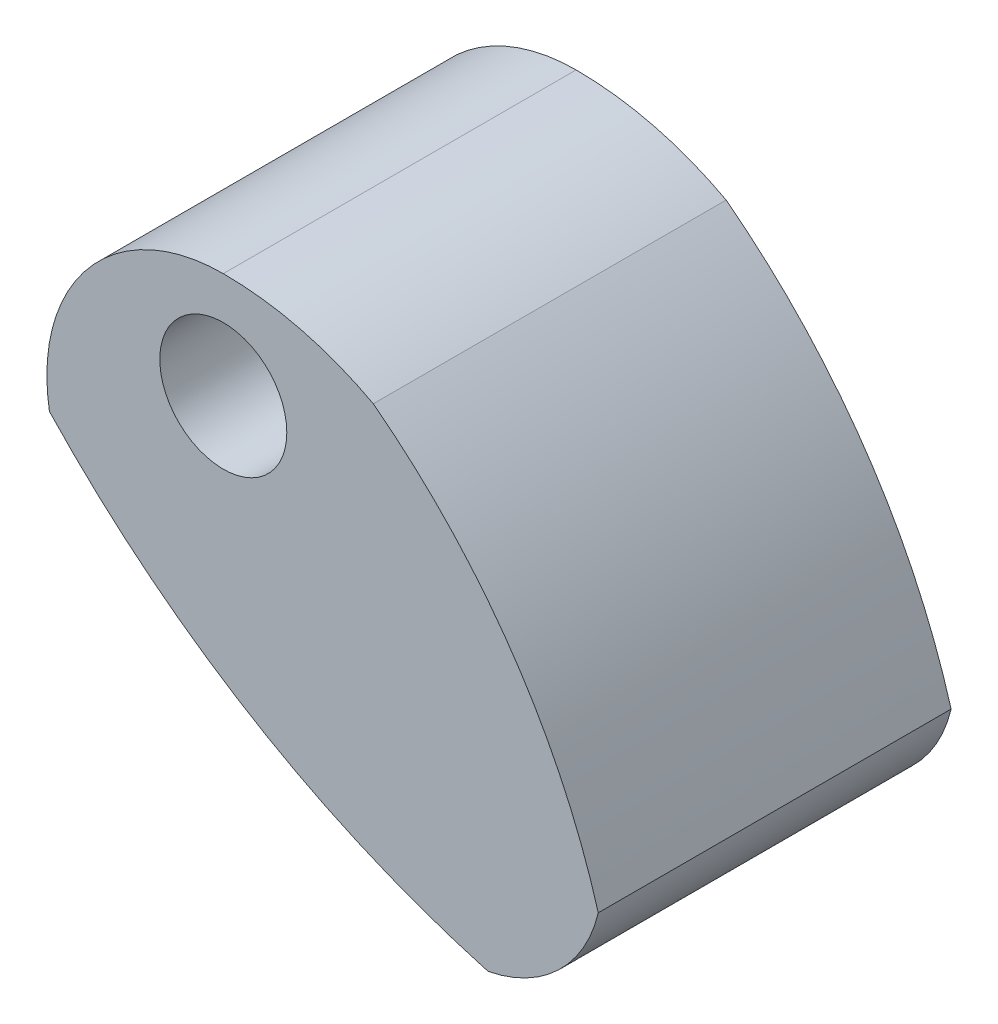
SolidWorks part; units mm, degrees
ref_plane "Front Plane" through (0, 0, 0) normal (0, 0, 1) x (1, 0, 0)
ref_plane "Top Plane" through (0, 0, 0) normal (0, 1, 0) x (1, 0, 0)
ref_plane "Right Plane" through (0, 0, 0) normal (1, 0, 0) x (0, 0, -1)
sketch "Sketch1" plane through (0, 0, 0) normal (0, 0, 1) x (1, 0, 0)
  line L1 (10.6276, -5.3741) -> (7.5046, -5.3741)
  arc A0 (-4.9277, -0.8474) -> (7.5046, -8.3741) centre (14.7558, 17.6339) ccw
  arc A2 (7.5046, -8.3741) -> (10.6276, -5.3741) centre (6.7362, -4.4486) ccw
  arc A4 (6.5977, -5.158) -> (-4.9277, -0.8474) centre (-26.404, -75.8325) ccw
  arc A5 (10.6276, -5.3741) -> (4.2517, 3.9324) centre (-6.6618, -10.3818) ccw
  arc A6 (0, 5) -> (-4.9277, -0.8474) centre (0, 0) ccw
  arc A7 (4.2517, 3.9324) -> (0, 5) centre (0, -4) ccw
  spline S1 degree 3 poles (6.5977, -5.158) (6.7404, -5.2246) (6.8871, -5.2773) (7.1896, -5.352) (7.3467, -5.3741) (7.5046, -5.3741) knots 0 0 0 0 0.5 0.5 1 1 1 1
  dimension "D1" = 9
  dimension "D2" = 5
  dimension "D3" = 18
  dimension "D4" = 78
  dimension "D15" = 4
  dimension "D16" = 27
  dimension "D5" = 4.2517
  dimension "D6" = 1.0676
  dimension "D7" = 9.3066
  dimension "D8" = 6.3759
  dimension "D9" = 3.123
  dimension "D10" = 0.2161
  dimension "D11" = 0.9069
  dimension "D12" = 11.5254
  dimension "D13" = 4.3106
  dimension "D14" = 5.8474
  dimension "D17" = 3
sketch "Sketch3" plane through (0, 0, 0) normal (0, 0, 1) x (1, 0, 0)
  arc A0 (7.5046, -8.3741) -> (10.6276, -5.3741) centre (6.7362, -4.4486) ccw construction
  arc A1 (10.6276, -5.3741) -> (4.2517, 3.9324) centre (-6.6618, -10.3818) ccw construction
  arc A2 (4.2517, 3.9324) -> (0, 5) centre (0, -4) ccw construction
  arc A3 (0, 5) -> (-4.9277, -0.8474) centre (0, 0) ccw construction
  arc A6 (10.6276, -5.3741) -> (4.2517, 3.9324) centre (-6.6618, -10.3818) ccw
  arc A7 (4.2517, 3.9324) -> (0, 5) centre (0, -4) ccw
  arc A8 (0, 5) -> (-4.9277, -0.8474) centre (0, 0) ccw
  arc A10 (-4.9277, -0.8474) -> (7.5046, -8.3741) centre (14.7558, 17.6339) ccw construction
  arc A11 (-4.9277, -0.8474) -> (7.5046, -8.3741) centre (14.7558, 17.6339) ccw
  arc A12 (7.5046, -8.3741) -> (10.6276, -5.3741) centre (6.7362, -4.4486) ccw
extrude "Boss-Extrude3" add sketch "Sketch3" along normal blind 10
sketch "Sketch5" plane through (0, 0, 0) normal (0, 0, 1) x (1, 0, 0)
  line L2 (6.5977, -5.158) -> (6.5977, 1.7914)
  line L4 (6.5977, -5.158) -> (6.5977, -8.1041)
  arc A0 (-4.9277, -0.8474) -> (7.5046, -8.3741) centre (14.7558, 17.6339) ccw construction
  arc A1 (0, 5) -> (-4.9277, -0.8474) centre (0, 0) ccw construction
  arc A2 (4.2517, 3.9324) -> (0, 5) centre (0, -4) ccw construction
  arc A3 (10.6276, -5.3741) -> (4.2517, 3.9324) centre (-6.6618, -10.3818) ccw construction
  arc A4 (6.5977, -5.158) -> (-4.9277, -0.8474) centre (-26.404, -75.8325) ccw construction
  arc A5 (-4.9277, -0.8474) -> (6.5977, -8.1041) centre (14.7558, 17.6339) ccw
  arc A6 (0, 5) -> (-4.9277, -0.8474) centre (0, 0) ccw
  arc A7 (4.2517, 3.9324) -> (0, 5) centre (0, -4) ccw
  arc A8 (6.5977, 1.7914) -> (4.2517, 3.9324) centre (-6.6618, -10.3818) ccw
  arc A9 (6.5977, -5.158) -> (-4.9277, -0.8474) centre (-26.404, -75.8325) ccw
sketch "Sketch4" plane through (0, 0, 0) normal (0, 0, 1) x (1, 0, 0)
  line L0 (10.6276, -5.3741) -> (7.5046, -5.3741) construction
  line L1 (10.6276, -5.3741) -> (7.5046, -5.3741)
  arc A0 (6.5977, -5.158) -> (-4.9277, -0.8474) centre (-26.404, -75.8325) ccw construction
  arc A1 (10.6276, -5.3741) -> (4.2517, 3.9324) centre (-6.6618, -10.3818) ccw construction
  arc A2 (4.2517, 3.9324) -> (0, 5) centre (0, -4) ccw construction
  arc A3 (0, 5) -> (-4.9277, -0.8474) centre (0, 0) ccw construction
  arc A4 (6.5977, -5.158) -> (-4.9277, -0.8474) centre (-26.404, -75.8325) ccw
  arc A5 (10.6276, -5.3741) -> (4.2517, 3.9324) centre (-6.6618, -10.3818) ccw
  arc A6 (4.2517, 3.9324) -> (0, 5) centre (0, -4) ccw
  arc A7 (0, 5) -> (-4.9277, -0.8474) centre (0, 0) ccw
  spline S0 degree 3 poles (-606.7237, -1908.4177) (37.8602, 238.379) (-11.6557, -0.699) (16.168, -7.5688) (46.9323, 45.4663) (-1045.0956, 1694.4171) knots -61.313464 -61.313464 -61.313464 -61.313464 0.5 0.5 30.687913 30.687913 30.687913 30.687913 only from (6.5977, -5.158) to (7.5046, -5.3741) construction
  spline S1 degree 3 poles (6.5977, -5.158) (6.7404, -5.2246) (6.8871, -5.2773) (7.1896, -5.352) (7.3467, -5.3741) (7.5046, -5.3741) knots 0 0 0 0 0.5 0.5 1 1 1 1
hole_wizard "M3 Clearance Hole1" positions "Sketch8" profile "Sketch7" hole size "M3" standard "ISO"
sketch "Sketch8" plane through (0, 0, 10) normal (0, 0, 1) x (1, 0, 0)
  point P0 (0, 2)
  dimension "D1" = 2
sketch "Sketch7" plane through (0, 2, 10) normal (1, 0, 0) x (0, -1, 0)
  line L0 (0, 0) -> (0, 6.0815)
  line L1 (0, 6.0815) -> (1.8, 5)
  line L2 (1.8, 5) -> (1.8, 0)
  line L5 (1.8, 0) -> (0, 0)
  line L10 (0, 6.0815) -> (-1.8, 5) construction
  line L11 (0, -6.35) -> (0, 107.95) construction
  dimension "Hole Dia." = 3.6
  dimension "Hole Depth" = 5
  dimension "Drill Angle" = 118
